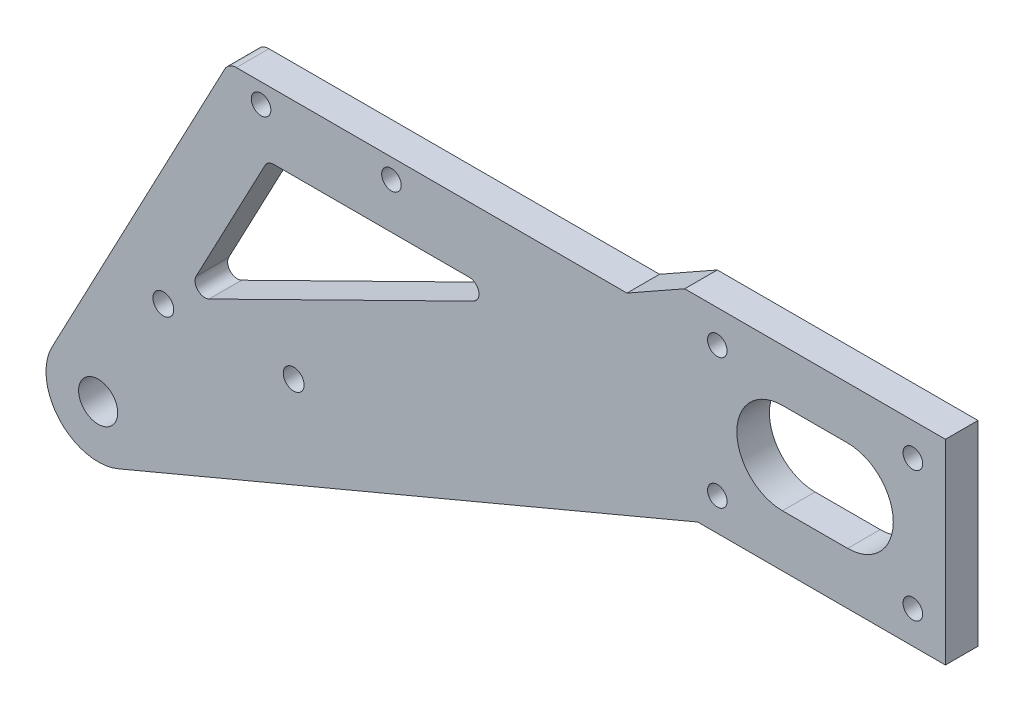
SolidWorks part; units mm, degrees
material "Thornel Mat VMA"
ref_plane "前视基准面" through (0, 0, 0) normal (0, 0, 1) x (1, 0, 0)
ref_plane "上视基准面" through (0, 0, 0) normal (0, 1, 0) x (1, 0, 0)
ref_plane "右视基准面" through (0, 0, 0) normal (1, 0, 0) x (0, 0, -1)
sketch "草图1" plane through (0, 0, 0) normal (0, 0, 1) x (1, 0, 0)
  line L0 (-3.9331, 6.9664) -> (90, 60)
  line L1 (90, 60) -> (130, 60)
  line L2 (130, 60) -> (130, 30)
  line L3 (92, 30) -> (3.1005, -7.3748)
  line L4 (92, 30) -> (130, 30)
  line L5 (125, 55) -> (95, 55) construction
  line L6 (125, 55) -> (125, 35) construction
  line L7 (125, 35) -> (95, 35) construction
  line L8 (95, 55) -> (95, 35) construction
  circle A0 centre (0, 0) radius 3
  arc A1 (-3.9331, 6.9664) -> (3.1005, -7.3748) centre (0, 0) ccw
  circle A2 centre (95, 55) radius 1.5
  circle A3 centre (125, 55) radius 1.5
  circle A4 centre (125, 35) radius 1.5
  circle A5 centre (95, 35) radius 1.5
  dimension "D1" = 6
  dimension "D2" = 40
  dimension "D6" = 8
  dimension "D7" = 5
  dimension "D11" = 3
  dimension "D3" = 30
  dimension "D4" = 60
  dimension "D5" = 90
  dimension "D8" = 5
  dimension "D9" = 5
  dimension "D10" = 5
  dimension "D12" = 3
extrude "凸台-拉伸1" add sketch "草图1" along normal blind 5
sketch "草图3" plane through (0, 0, 5) normal (0, 0, 1) x (1, 0, 0)
  line L0 (81.144, 55) -> (20, 55)
  line L1 (90, 60) -> (-3.9331, 6.9664) construction
  line L2 (20, 55) -> (20, 20.4788)
  line L3 (20, 20.4788) -> (81.144, 55)
  line L4 (92, 30) -> (130, 30) construction
  circle A0 centre (95, 55) radius 1.5 construction
  dimension "D1" = 25
  dimension "D2" = 75
extrude "凸台-拉伸2" add sketch "草图3" against normal up to surface (5 mm away) up to face at (72.4002, 29.3788, 0)
sketch "草图4" plane through (0, 0, 5) normal (0, 0, 1) x (1, 0, 0)
  line L0 (25, 52) -> (45, 52) construction
  line L1 (81.144, 55) -> (20, 55) construction
  circle A0 centre (25, 52) radius 1.5
  circle A1 centre (45, 52) radius 1.5
  circle A2 centre (95, 55) radius 1.5 construction
  dimension "D1" = 3
  dimension "D4" = 3
  dimension "D2" = 20
  dimension "D3" = 50
extrude "切除-拉伸1" cut sketch "草图4" against normal through all
sketch "草图6" plane through (0, 0, 5) normal (0, 0, 1) x (1, 0, 0)
  line L0 (-7.074, 3.736) -> (20, 55)
  line L1 (20, 55) -> (20, 20.4788) construction
  line L2 (20, 20.4788) -> (-3.9331, 6.9664) construction
  line L3 (20, 55) -> (20, 20.4788)
  line L4 (20, 20.4788) -> (-3.9331, 6.9664)
  arc A0 (-3.9331, 6.9664) -> (3.1005, -7.3748) centre (0, 0) ccw construction
  arc A1 (-3.9331, 6.9664) -> (-7.074, 3.736) centre (0, 0) ccw
extrude "凸台-拉伸3" add sketch "草图6" against normal up to surface (5 mm away) up to face at (26.5, 52, 0)
sketch "草图5" plane through (0, 0, 5) normal (0, 0, 1) x (1, 0, 0)
  line L3 (20, 55) -> (-7.074, 3.736) construction
  line L10 (81.144, 55) -> (20, 55) construction
  line L11 (105, 45) -> (115, 45) construction
  line L12 (95, 55) -> (125, 55) construction
  line L13 (95, 55) -> (95, 35) construction
  line L14 (95, 35) -> (125, 35) construction
  line L15 (125, 55) -> (125, 35) construction
  line L16 (105, 52) -> (115, 52)
  line L17 (105, 38) -> (115, 38)
  line L21 (25.6054, 44.2005) -> (15.0428, 24.2005)
  line L22 (17.0325, 22.1546) -> (57.5951, 42.1546)
  line L24 (56.9318, 45) -> (26.9318, 45)
  arc A11 (105, 52) -> (105, 38) centre (105, 45) ccw
  arc A12 (115, 38) -> (115, 52) centre (115, 45) ccw
  arc A13 (57.5951, 42.1546) -> (56.9318, 45) centre (56.9318, 43.5) ccw
  arc A14 (15.0428, 24.2005) -> (17.0325, 22.1546) centre (16.3692, 23.5) ccw
  arc A15 (25.6054, 44.2005) -> (26.9318, 45) centre (26.9318, 43.5) cw
  point P15 (0, 0)
  point P29 (110, 45)
  point P30 (110, 55)
  point P53 (95, 45)
  dimension "D3" = 10
  dimension "D10" = 7
  dimension "D4" = 1.5
  dimension "D8" = 30
  dimension "D2" = 10
  dimension "D11" = 10
  dimension "D12" = 20
extrude "切除-拉伸2" cut sketch "草图5" against normal through all
sketch "草图7" plane through (0, 0, 5) normal (0, 0, 1) x (1, 0, 0)
  line L0 (10, 18) -> (30, 18) construction
  circle A0 centre (10, 18) radius 1.6
  circle A1 centre (30, 18) radius 1.6
  dimension "D2" = 3.2
  dimension "D1" = 20
  dimension "D3" = 10
  dimension "D4" = 18
extrude "切除-拉伸3" cut sketch "草图7" against normal through all
fillet "圆角1" radius 2 1 edges at (20, 55, 2.5)
